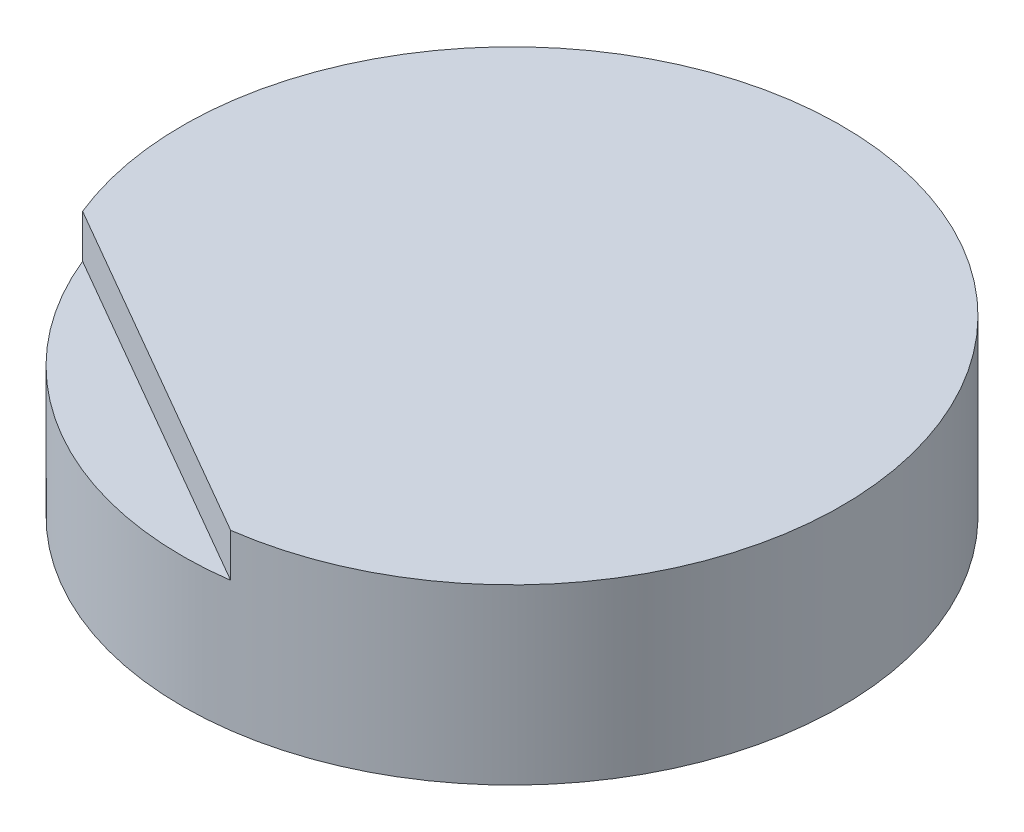
SolidWorks part; units mm, degrees
other "Fixed Steel Cup Liner 2"
ref_plane "Front Plane" through (0, 0, 0) normal (0, 0, 1) x (1, 0, 0)
ref_plane "Top Plane" through (0, 0, 0) normal (0, 1, 0) x (1, 0, 0)
ref_plane "Right Plane" through (0, 0, 0) normal (1, 0, 0) x (0, 0, -1)
sketch3d "Keyed Back Sketch datum points"
  point P0 (-56.2917, -69, 0)
  point P1 (-46.2917, -69, 0)
  point P2 (-56.2917, -69, 10)
ref_plane "Keyed Back Sketch plane" through (0, -69, 0) normal (0, -1, 0) x (-1, 0, 0)
sketch "Keyed Back Sketch" plane through (0, -69, 0) normal (0, -1, 0) x (-1, 0, 0)
  line L0 (70.7718, -29.745) -> (74.8116, -27.4126)
  arc A0 (74.8116, -27.4126) -> (70.7718, -29.745) centre (71.2917, -25.9808) ccw
extrude "Keyed Back" add sketch "Keyed Back Sketch" along normal blind 0.5 separate body
sketch3d "Cup Blank Sketch datum points"
  point P0 (-56.2917, -69.5, 0)
  point P1 (-46.2917, -69.5, 0)
  point P2 (-56.2917, -69.5, 10)
ref_plane "Cup Blank Sketch plane" through (0, -69.5, 0) normal (0, -1, 0) x (-1, 0, 0)
sketch "Cup Blank Sketch" plane through (0, -69.5, 0) normal (0, -1, 0) x (-1, 0, 0)
  circle A0 centre (71.2917, -25.9808) radius 3.8
extrude "Cup Blank" add sketch "Cup Blank Sketch" along normal blind 1.5
sketch3d "Spherical Bearing Seat axis line"
  line L0 (-71.2917, -73, 15.9808) -> (-71.2917, -73, 35.9808) construction
ref_axis "Spherical Bearing Seat axis" through (-71.2917, -73, 15.9808) along (0, 0, 1)
sketch3d "Spherical Bearing Seat profile datum points"
  point P0 (-71.2917, -73, 25.9808)
  point P1 (-61.2917, -73, 25.9808)
  point P2 (-71.2917, -73, 35.9808)
ref_plane "Spherical Bearing Seat profile plane" through (0, -73, 0) normal (0, -1, 0) x (-1, 0, 0)
sketch "Spherical Bearing Seat profile" plane through (0, -73, 0) normal (0, -1, 0) x (-1, 0, 0)
  line L0 (71.2917, -29.0808) -> (71.2917, -22.8808)
  arc A0 (71.2917, -22.8808) -> (71.2917, -29.0808) centre (71.2917, -25.9808) ccw
revolve "Spherical Bearing Seat" cut sketch "Spherical Bearing Seat profile" angle 360 about axis through (-71.2917, -73, 15.9808) along (0, 0, 1)
